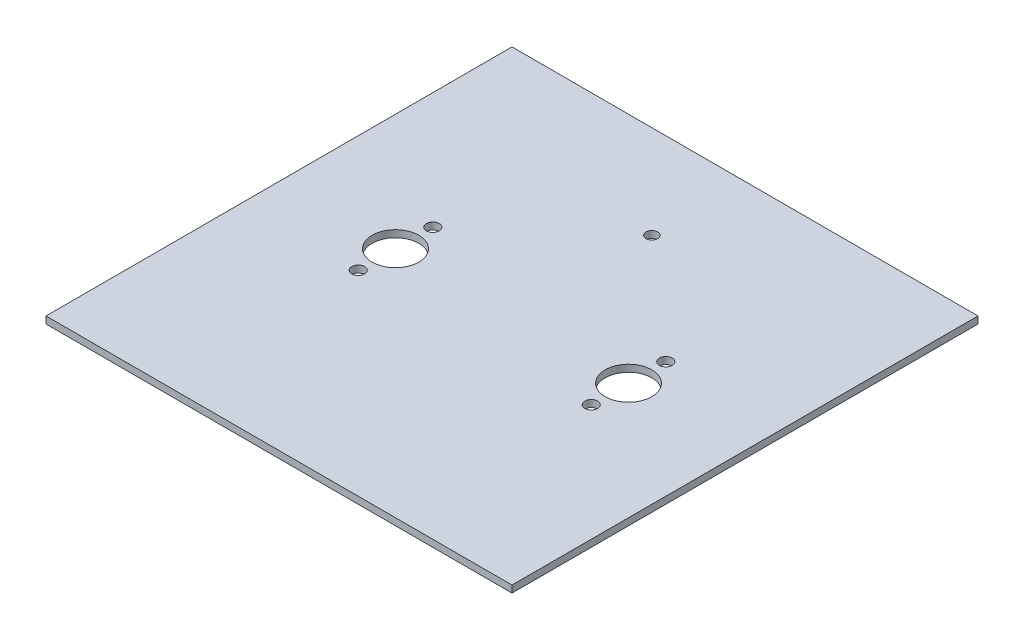
SolidWorks part; units mm, degrees
ref_plane "前视基准面" through (0, 0, 0) normal (0, 0, 1) x (1, 0, 0)
ref_plane "上视基准面" through (0, 0, 0) normal (0, 1, 0) x (1, 0, 0)
ref_plane "右视基准面" through (0, 0, 0) normal (1, 0, 0) x (0, 0, -1)
sketch "草图1" plane through (0, 0, 0) normal (0, 1, 0) x (1, 0, 0)
  line L0 (-100, 100) -> (100, 100)
  line L1 (-100, -100) -> (100, -100)
  line L2 (-100, 100) -> (-100, -100)
  line L3 (100, 100) -> (100, -100)
  circle A0 centre (0, 60) radius 2.5
  circle A6 centre (50, 0) radius 10
  circle A7 centre (50, 16) radius 2.75
  circle A8 centre (50, -16) radius 2.75
  circle A9 centre (-50, -16) radius 2.75
  circle A10 centre (-50, 16) radius 2.75
  circle A11 centre (-50, 0) radius 10
extrude "凸台-拉伸1" add sketch "草图1" along normal blind 3
